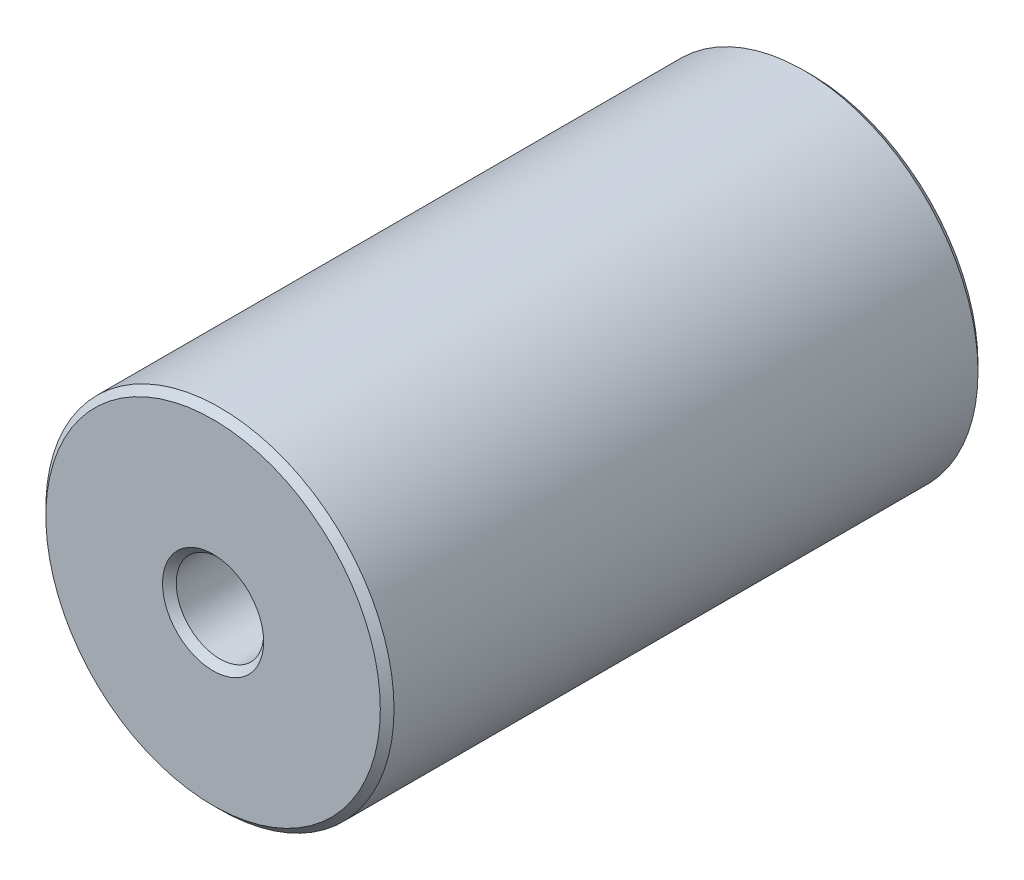
SolidWorks part; units mm, degrees
ref_plane "Front Plane" through (0, 0, 0) normal (0, 0, 1) x (1, 0, 0)
ref_plane "Top Plane" through (0, 0, 0) normal (0, 1, 0) x (1, 0, 0)
ref_plane "Right Plane" through (0, 0, 0) normal (1, 0, 0) x (0, 0, -1)
sketch "Sketch1" plane through (0, 0, 0) normal (0, 0, 1) x (1, 0, 0)
  circle A0 centre (0, 0) radius 12.7
  dimension "D1" = 25.4
extrude "Boss-Extrude1" add sketch "Sketch1" along normal blind 43.6
sketch "Sketch2" plane through (0, 0, 43.6) normal (0, 0, 1) x (1, 0, 0)
  circle A0 centre (0, 0) radius 3.1877
  dimension "D1" = 6.3754
extrude "Cut-Extrude1" cut sketch "Sketch2" against normal through all
hole_wizard "5/16 (0.3125) Diameter Hole1" positions "3DSketch3" profile "Sketch6" hole size "5/16" standard "Ansi Inch"
sketch3d "3DSketch3"
  point P0 (0, 0, 0)
  point P2 (0, 0, 0)
sketch "Sketch6" plane through (0, 0, 0) normal (1, 0, 0) x (0, 1, 0)
  line L0 (0, 0) -> (0, 21.1143)
  line L1 (0, 21.1143) -> (3.8583, 18.796)
  line L2 (3.8583, 18.796) -> (3.8583, 0)
  line L5 (3.8583, 0) -> (0, 0)
  line L10 (0, 21.1143) -> (-3.8583, 18.796) construction
  line L11 (0, -6.35) -> (0, 107.95) construction
  dimension "Hole Dia." = 7.7165
  dimension "Hole Depth" = 18.796
  dimension "Drill Angle" = 118
chamfer "Chamfer1" distance 0.5 angle 45 2 edges at (12.7, 0, 43.6) (12.7, 0, 0)
chamfer "Chamfer2" distance 0.5 angle 45 1 edges at (3.1877, 0, 43.6)
